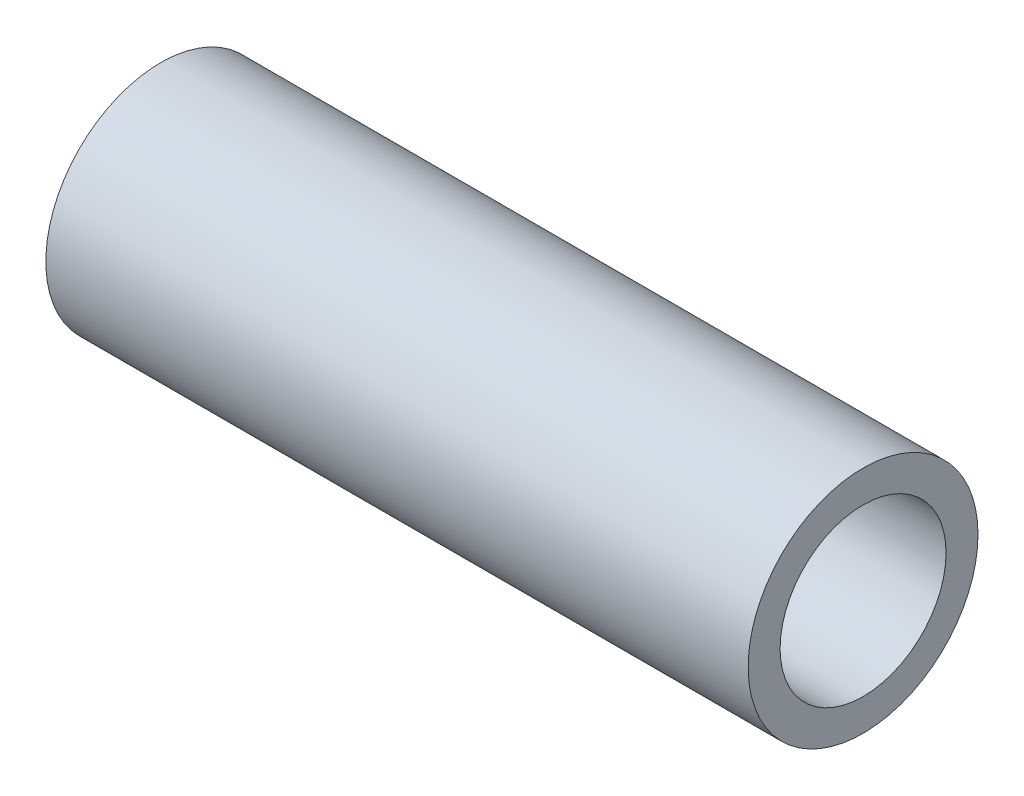
SolidWorks part; units mm, degrees
ref_plane "Front Plane" through (0, 0, 0) normal (0, 0, 1) x (1, 0, 0)
ref_plane "Top Plane" through (0, 0, 0) normal (0, 1, 0) x (1, 0, 0)
ref_plane "Right Plane" through (0, 0, 0) normal (1, 0, 0) x (0, 0, -1)
sketch "Sketch1" plane through (0, 0, 0) normal (1, 0, 0) x (0, 0, -1)
  circle A0 centre (0, 0) radius 6.5
  circle A1 centre (0, 0) radius 9
  dimension "D1" = 13
  dimension "D2" = 18
extrude "Boss-Extrude1" add sketch "Sketch1" along normal mid plane 55
